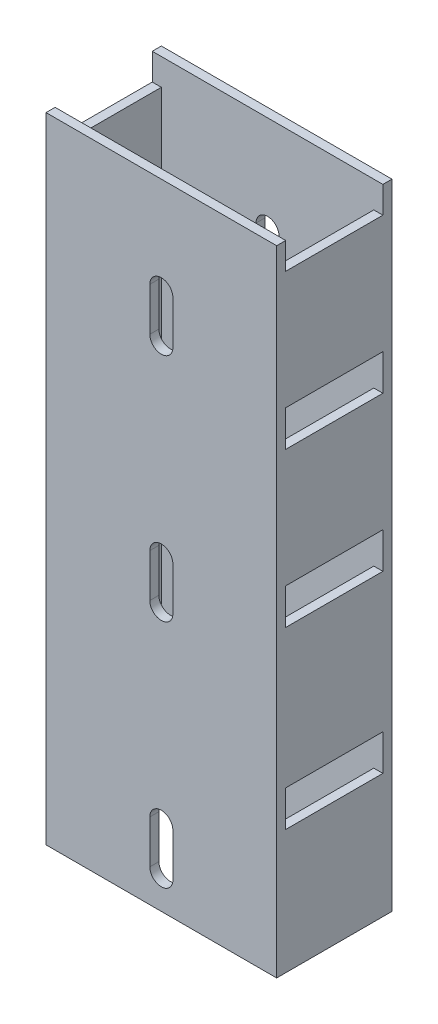
SolidWorks part; units mm, degrees
ref_plane "Front Plane" through (0, 0, 0) normal (0, 0, 1) x (1, 0, 0)
ref_plane "Top Plane" through (0, 0, 0) normal (0, 1, 0) x (1, 0, 0)
ref_plane "Right Plane" through (0, 0, 0) normal (1, 0, 0) x (0, 0, -1)
sketch "Sketch1" plane through (0, 0, 0) normal (0, 1, 0) x (1, 0, 0)
  line L0 (0, 25.4) -> (50.8, 0) construction
  line L1 (0, 0) -> (50.8, 0)
  line L2 (0, 0) -> (0, 25.4)
  line L3 (0, 25.4) -> (50.8, 25.4)
  line L4 (50.8, 0) -> (50.8, 25.4)
  line L6 (2, 23.4) -> (48.8, 23.4)
  line L7 (2, 23.4) -> (2, 2)
  line L8 (2, 2) -> (48.8, 2)
  line L9 (48.8, 23.4) -> (48.8, 2)
  line L10 (2, 23.4) -> (48.8, 2) construction
  line L11 (2, 2) -> (48.8, 23.4) construction
  point P5 (25.4, 12.7)
  dimension "D1" = 50.8
  dimension "D2" = 25.4
  dimension "D3" = 2
  dimension "D4" = 2
extrude "Boss-Extrude1" add sketch "Sketch1" against normal blind 139.7
sketch "Sketch2" plane through (50.8, 0, 0) normal (1, 0, 0) x (0, 0, -1)
  line L0 (2, -139.7) -> (2, 0) construction
  line L1 (2, -139.7) -> (2, 0)
  line L2 (23.4, -139.7) -> (23.4, 0) construction
  line L3 (23.4, -139.7) -> (23.4, 0)
  line L4 (23.4, -69.85) -> (2, -69.85) construction
  line L6 (2, -65.8813) -> (23.4, -65.8813)
  line L7 (2, -65.8813) -> (2, -73.8187)
  line L8 (2, -73.8187) -> (23.4, -73.8187)
  line L9 (23.4, -65.8813) -> (23.4, -73.8187)
  line L10 (2, -65.8813) -> (23.4, -73.8187) construction
  line L11 (2, -73.8187) -> (23.4, -65.8813) construction
  point P6 (12.7, -69.85)
  dimension "D1" = 7.9375
extrude "Cut-Extrude1" cut sketch "Sketch2" against normal through all contours L1 L8 L3 L6
pattern_linear "LPattern1" count 3 spacing 33.9725 along (0, 1, 0) count 2 spacing 38.5445 along (0, -1, 0) of "Cut-Extrude1"
sketch "Sketch3" plane through (0, 0, -25.4) normal (0, 0, -1) x (-1, 0, 0)
  line L0 (-25.4, 0) -> (-25.4, -139.7) construction
  line L1 (-25.4, -21.336) -> (-25.4, -30.861) construction
  line L2 (-22.86, -21.336) -> (-22.86, -30.861)
  line L3 (-27.94, -21.336) -> (-27.94, -30.861)
  line L4 (-50.8, -139.7) -> (0, -139.7)
  line L5 (0, -139.7) -> (0, 0)
  line L6 (0, 0) -> (-50.8, 0)
  line L7 (-50.8, 0) -> (-50.8, -139.7)
  line L8 (-50.8, -139.7) -> (0, -139.7) construction
  line L9 (0, -139.7) -> (0, 0) construction
  line L10 (0, 0) -> (-50.8, 0) construction
  line L11 (-50.8, 0) -> (-50.8, -139.7) construction
  arc A0 (-22.86, -21.336) -> (-27.94, -21.336) centre (-25.4, -21.336) ccw
  arc A1 (-27.94, -30.861) -> (-22.86, -30.861) centre (-25.4, -30.861) ccw
  point P8 (-25.4, -26.0985)
  point P13 (-25.4, -18.796)
  point P14 (-25.4, -33.401)
  dimension "D3" = 2.54
  dimension "D2" = 18.796
  dimension "D4" = 14.605
  dimension "D1" = 0
extrude "Cut-Extrude2" cut sketch "Sketch3" against normal through all
pattern_linear "LPattern2" count 3 spacing 50.8 along (0, -1, 0) of "Cut-Extrude2"
ref_plane "Plane1" through (25.4, 0, 0) normal (-1, 0, 0) x (0, 0, 1)
ref_plane "Plane2" through (0, -69.85, 0) normal (0, 1, 0) x (1, 0, 0)
